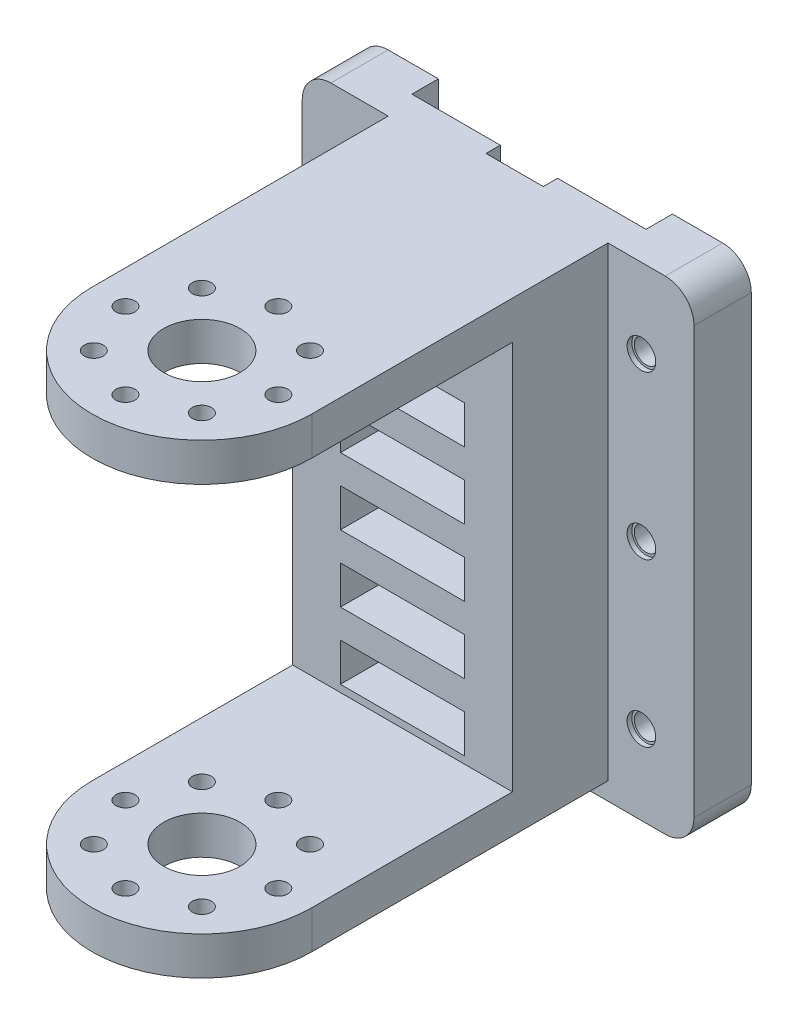
SolidWorks part; units mm, degrees
ref_plane "Front Plane" through (0, 0, 0) normal (0, 0, 1) x (1, 0, 0)
ref_plane "Top Plane" through (0, 0, 0) normal (0, 1, 0) x (1, 0, 0)
ref_plane "Right Plane" through (0, 0, 0) normal (1, 0, 0) x (0, 0, -1)
sketch "Sketch1" plane through (0, 0, 0) normal (0, 0, 1) x (1, 0, 0)
  line L1 (-20.5, 25.3) -> (20.5, 25.3)
  line L2 (-20.5, 25.3) -> (-20.5, -25.3)
  line L3 (-20.5, -25.3) -> (20.5, -25.3)
  line L4 (20.5, 25.3) -> (20.5, -25.3)
  line L5 (-20.5, 25.3) -> (20.5, -25.3) construction
  line L6 (-20.5, -25.3) -> (20.5, 25.3) construction
  point P0 (0, 0)
  dimension "D1" = 50.6
  dimension "D2" = 41
extrude "Boss-Extrude1" add sketch "Sketch1" along normal blind 6
fillet "Fillet1" radius 3 4 edges at (-20.5, -25.3, 3) (20.5, -25.3, 3) (-20.5, 25.3, 3) (20.5, 25.3, 3)
sketch "Sketch3" plane through (0, 0, 6) normal (0, 0, 1) x (1, 0, 0)
  circle A0 centre (-15, 0) radius 1.25
  circle A1 centre (-5, 0) radius 1.25 [skipped]
  circle A2 centre (-5, 17) radius 1.25 [skipped]
  circle A3 centre (-15, 17) radius 1.25
  circle A4 centre (-15, -17) radius 1.25
  point P2 (0, 0)
  point P5 (0, 0)
  dimension "D2" = 2.5
  dimension "D1" = 15
  dimension "D7" = 17
  dimension "D8" = 17
  dimension "D4" = 2
  dimension "D5" = 2
  dimension "D6" = 2
extrude "Cut-Extrude1" cut sketch "Sketch3" against normal through all
mirror "Mirror1" about plane through (0, 0, 0) normal (1, 0, 0) of "Cut-Extrude1"
sketch "Sketch4" plane through (0, 0, 6) normal (0, 0, 1) x (1, 0, 0)
  circle A0 centre (-15, 17) radius 1.5
  circle A1 centre (-15, 0) radius 1.5
  circle A2 centre (-15, -17) radius 1.5
  point P3 (0, 0)
  point P4 (-15, 2.8)
  dimension "D1" = 3
  dimension "D2" = 3
extrude "Cut-Extrude2" cut sketch "Sketch4" against normal blind 0.5
mirror "Mirror2" about plane through (0, 0, 0) normal (1, 0, 0) of "Cut-Extrude2"
sketch "Sketch5" plane through (0, 0, 0) normal (0, 0, -1) x (-1, 0, 0)
  line L0 (-17.5, 25.3) -> (17.5, 25.3) construction
  line L1 (-12.25, 25.3) -> (12.25, 25.3)
  line L2 (-12.25, 25.3) -> (-12.25, -20.7)
  line L3 (-12.25, -20.7) -> (12.25, -20.7)
  line L4 (12.25, 25.3) -> (12.25, -20.7)
  point P6 (0, -20.7)
  dimension "D1" = 46
  dimension "D2" = 24.5
extrude "Cut-Extrude3" cut sketch "Sketch5" against normal blind 2.77
sketch "Sketch6" plane through (0, 0, 2.77) normal (0, 0, -1) x (-1, 0, 0)
  line L0 (12.25, 25.3) -> (-12.25, 25.3) construction
  line L1 (-3, 25.3) -> (3, 25.3)
  line L2 (-3, 25.3) -> (-3, 9.3)
  line L3 (-3, 9.3) -> (3, 9.3)
  line L4 (3, 25.3) -> (3, 9.3)
  point P6 (0, 9.3)
  dimension "D1" = 6
  dimension "D2" = 16
extrude "Cut-Extrude4" cut sketch "Sketch6" against normal blind 1.5
sketch "Sketch7" plane through (0, 0, 6) normal (0, 0, 1) x (1, 0, 0)
  line L0 (17.5, 25.3) -> (-17.5, 25.3) construction
  line L1 (-11.5, 25.3) -> (11.5, 25.3)
  line L2 (-11.5, 25.3) -> (-11.5, -23.45)
  line L3 (-11.5, -23.45) -> (11.5, -23.45)
  line L4 (11.5, 25.3) -> (11.5, -23.45)
  line L5 (0, 25.3) -> (0, -25.3) construction
  line L6 (-17.5, -25.3) -> (17.5, -25.3) construction
  line L7 (-6.5, 9.3004) -> (6.5, 9.3004)
  line L8 (-6.5, 20.3005) -> (6.5, 20.3005)
  line L9 (-6.5, 20.3005) -> (-6.5, 16.3004)
  line L10 (-6.5, 16.3004) -> (6.5, 16.3004)
  line L11 (6.5, 20.3005) -> (6.5, 16.3004)
  line L12 (6.5, 13.3005) -> (6.5, 9.3004)
  line L13 (-6.5, 13.3005) -> (6.5, 13.3005)
  line L14 (-6.5, 13.3005) -> (-6.5, 9.3004)
  line L15 (-6.5, 2.3004) -> (6.5, 2.3004)
  line L16 (6.5, 6.3005) -> (6.5, 2.3004)
  line L17 (-6.5, 6.3005) -> (6.5, 6.3005)
  line L18 (-6.5, 6.3005) -> (-6.5, 2.3004)
  line L19 (-6.5, -4.6996) -> (6.5, -4.6996)
  line L20 (6.5, -0.6995) -> (6.5, -4.6996)
  line L21 (-6.5, -0.6995) -> (6.5, -0.6995)
  line L22 (-6.5, -0.6995) -> (-6.5, -4.6996)
  line L23 (-6.5, -11.6996) -> (6.5, -11.6996)
  line L24 (6.5, -7.6995) -> (6.5, -11.6996)
  line L25 (-6.5, -7.6995) -> (6.5, -7.6995)
  line L26 (-6.5, -7.6995) -> (-6.5, -11.6996)
  line L27 (-6.5, -18.6996) -> (6.5, -18.6996)
  line L28 (6.5, -14.6995) -> (6.5, -18.6996)
  line L29 (-6.5, -14.6995) -> (6.5, -14.6995)
  line L30 (-6.5, -14.6995) -> (-6.5, -18.6996)
  circle A0 centre (15, 17) radius 1.5 construction
  point P12 (0, 16.3004)
  dimension "D1" = 3.5
  dimension "D2" = 48.75
  dimension "D3" = 13
  dimension "D4" = 4.9995
  dimension "D5" = 4.0001
  dimension "D7" = 2.9999
  dimension "D6" = 6
extrude "Boss-Extrude2" add sketch "Sketch7" along normal blind 10
sketch "Sketch8" plane through (0, 0, 16) normal (0, 0, 1) x (1, 0, 0)
  line L0 (11.5, -23.45) -> (11.5, 25.3) construction
  line L1 (-11.5, 25.3) -> (11.5, 25.3)
  line L2 (-11.5, 25.3) -> (-11.5, 21.3)
  line L3 (-11.5, 21.3) -> (11.5, 21.3)
  line L4 (11.5, 25.3) -> (11.5, 21.3)
  line L6 (-11.5, -23.45) -> (11.5, -23.45)
  line L7 (-11.5, -23.45) -> (-11.5, -19.45)
  line L8 (-11.5, -19.45) -> (11.5, -19.45)
  line L9 (11.5, -23.45) -> (11.5, -19.45)
  dimension "D1" = 4
  dimension "D2" = 4
extrude "Boss-Extrude3" add sketch "Sketch8" along normal blind 44
sketch "Sketch9" plane through (0, 25.3, 0) normal (0, 1, 0) x (1, 0, 0)
  line L0 (11.5, -60) -> (11.5, -6) construction
  line L1 (11.5, -60) -> (-11.5, -60) construction
  line L2 (-11.5, -60) -> (-11.5, -6) construction
  line L3 (11.5, -37) -> (-11.5, -37) construction
  arc A0 (-11.5, -37) -> (11.5, -37) centre (0, -37) ccw
  circle A1 centre (0, -37) radius 4
  circle A2 centre (0, -29) radius 1
  circle A3 centre (5.6569, -31.3431) radius 1
  circle A4 centre (8, -37) radius 1
  circle A5 centre (5.6569, -42.6569) radius 1
  circle A6 centre (0, -45) radius 1
  circle A7 centre (-5.6569, -42.6569) radius 1
  circle A8 centre (-8, -37) radius 1
  circle A9 centre (-5.6569, -31.3431) radius 1
  point P1 (0, 0)
  point P27 (0, -37)
  line M11 (-11.5, -6) -> (-11.5, -60)
  line M12 (-11.5, -60) -> (11.5, -60)
  line M13 (11.5, -60) -> (11.5, -6)
  dimension "D2" = 8
  dimension "D3" = 2
  dimension "D1" = 23
  dimension "D4" = 8
  dimension "D5" = 8
extrude "Cut-Extrude5" cut sketch "Sketch9" against normal through all contours A0 M11 M12 M13 | L3 A1 | A2 | A9 | L3 A8 | A7 | A8 L3 | A6 | A5 | A4 L3 | L3 A4 | A3 | A1 L3
